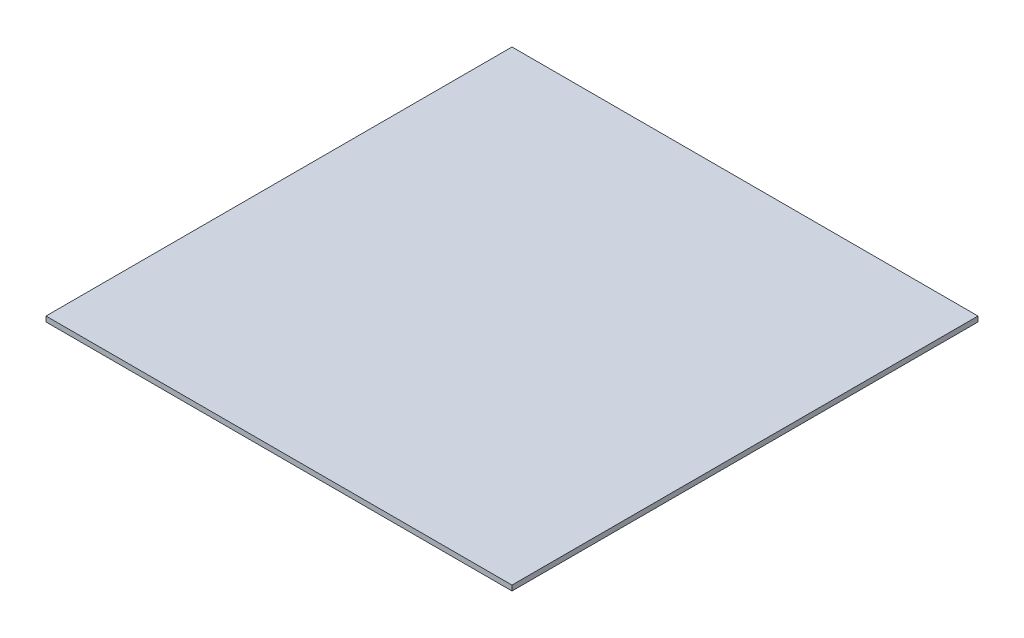
SolidWorks part; units mm, degrees
material "ABS PC"
ref_plane "Front Plane" through (0, 0, 0) normal (0, 0, 1) x (1, 0, 0)
ref_plane "Top Plane" through (0, 0, 0) normal (0, 1, 0) x (1, 0, 0)
ref_plane "Right Plane" through (0, 0, 0) normal (1, 0, 0) x (0, 0, -1)
sketch "Sketch1" plane through (0, 0, 0) normal (0, 1, 0) x (1, 0, 0)
  line L1 (450, -450) -> (-450, -450)
  line L2 (450, -450) -> (450, 450)
  line L3 (450, 450) -> (-450, 450)
  line L4 (-450, -450) -> (-450, 450)
  line L5 (450, -450) -> (-450, 450) construction
  line L6 (450, 450) -> (-450, -450) construction
  point P0 (0, 0)
  dimension "D1" = 900
  dimension "D2" = 900
extrude "Boss-Extrude1" add sketch "Sketch1" along normal blind 10
